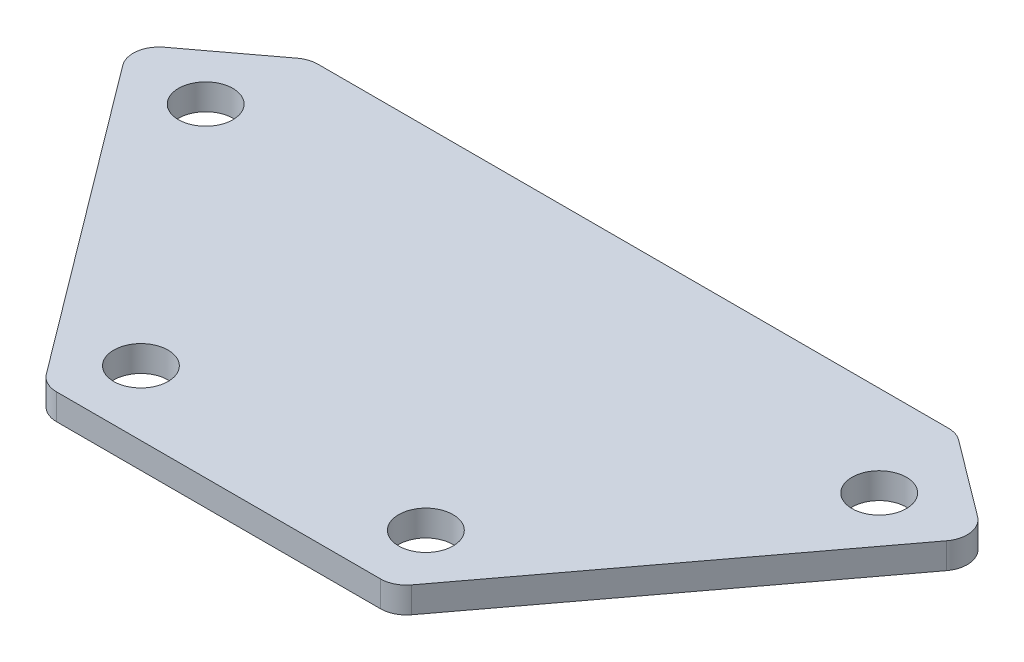
SolidWorks part; units mm, degrees
material "5052-H34"
ref_plane "正面" through (0, 0, 0) normal (0, 0, 1) x (1, 0, 0)
ref_plane "平面" through (0, 0, 0) normal (0, 1, 0) x (1, 0, 0)
ref_plane "右側面" through (0, 0, 0) normal (1, 0, 0) x (0, 0, -1)
sketch "ｽｹｯﾁ1" plane through (0, 0, 0) normal (0, 1, 0) x (1, 0, 0)
  line L0 (0, 0) -> (15, 0) construction
  line L1 (15, 0) -> (-15, 20) construction
  line L2 (-15, 20) -> (0, 0) construction
  line L3 (-15, 20) -> (-15, 0) construction
  line L4 (-15, 0) -> (0, 0) construction
  line L5 (-14, 27) -> (-2.5, 11.6667) construction
  line L6 (-14, 27) -> (-22, 21)
  line L7 (7, -1) -> (-1, -7)
  line L8 (-22, 21) -> (-1, -7)
  line L9 (-14, 27) -> (-1, -7) construction
  line L10 (7, -1) -> (-22, 21) construction
  line L11 (11, 10.8235) -> (20, 5) construction
  line L12 (-5, 5) -> (-3.75, 5) construction
  line L13 (-5, -1.6667) -> (-5, -5)
  line L14 (-5, -5) -> (20, -5)
  line L15 (20, 5) -> (20, -5)
  line L16 (-5, 5) -> (20, -5) construction
  line L17 (-5, -5) -> (20, 5) construction
  line L18 (-0.9091, 5) -> (2.5, 5) construction
  line L19 (7.5, 5) -> (20, 5) construction
  line L20 (2.5, 5) -> (7.5, 5) construction
  line L21 (-2.5, 11.6667) -> (2.5, 5) construction
  line L22 (6.5385, -0.3846) -> (7, -1) construction
  line L23 (2.5, 5) -> (5.7143, 0.7143) construction
  line L24 (5.7143, 0.7143) -> (6.25, 0) construction
  line L25 (6.25, 0) -> (6.5385, -0.3846) construction
  line L26 (-3.75, 5) -> (-0.9091, 5) construction
  line L27 (-5, 5) -> (-5, 3.4615) construction
  line L28 (-5, 3.4615) -> (-5, 0) construction
  line L29 (-5, 0) -> (-5, -1.6667) construction
  line L30 (0, 0) -> (11, 0) construction
  line L31 (11, 0) -> (11, 20) construction
  line L32 (27, -5) -> (2, -5)
  line L33 (36, 27) -> (44, 21)
  line L34 (44, 21) -> (23, -7)
  line L35 (36, 27) -> (-14, 27)
  line L36 (-14, 27) -> (11, 10.8235) construction
  circle A0 centre (0, 0) radius 2.1
  circle A1 centre (-15, 20) radius 2.1
  circle A2 centre (15, 0) radius 2.1 construction
  circle A3 centre (37, 20) radius 2.1
  circle A4 centre (22, 0) radius 2.1
  point P9 (-7.5, 10)
  point P10 (7.5, 0)
  dimension "D1" = 4.2
  dimension "D2" = 15
  dimension "D3" = 25
  dimension "D4" = 20
  dimension "D5" = 10
  dimension "D6" = 5
  dimension "D7" = 5
  dimension "D8" = 22
extrude "ﾎﾞｽ - 押し出し2" add sketch "ｽｹｯﾁ1" along normal blind 2
fillet "ﾌｨﾚｯﾄ1" radius 2 6 edges at (-22, 1, -21) (-14, 1, -27) (36, 1, -27) (44, 1, -21) (24.5, 1, 5) (-2.5, 1, 5)
